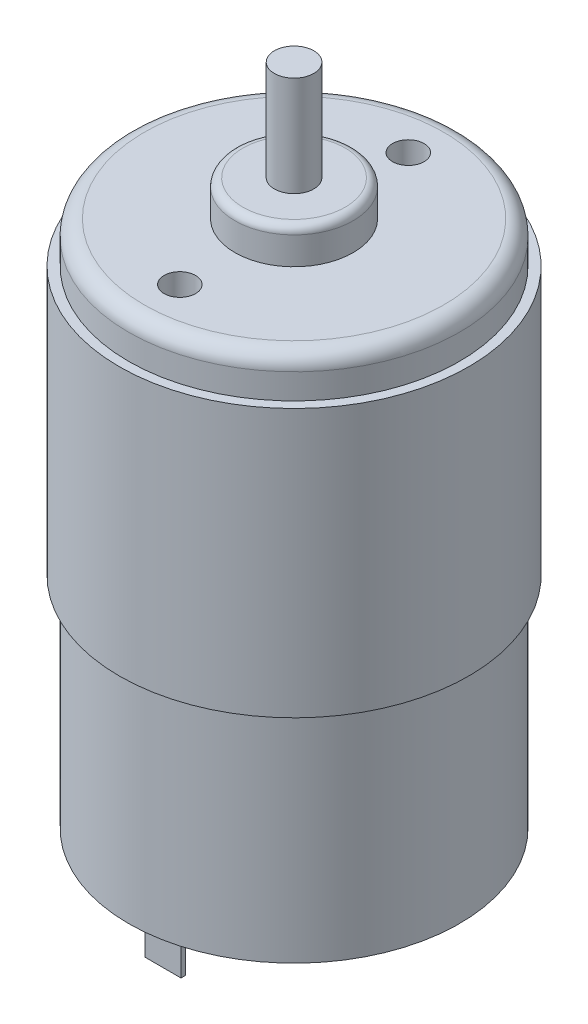
SolidWorks part; units mm, degrees
ref_plane "정면" through (0, 0, 0) normal (0, 0, 1) x (1, 0, 0)
ref_plane "윗면" through (0, 0, 0) normal (0, 1, 0) x (1, 0, 0)
ref_plane "우측면" through (0, 0, 0) normal (1, 0, 0) x (0, 0, -1)
sketch "스케치1" plane through (0, 0, 0) normal (0, 1, 0) x (1, 0, 0)
  circle A0 centre (0, 0) radius 21
  dimension "D1" = 42
extrude "보스-돌출1" add sketch "스케치1" along normal blind 67
sketch "스케치3" plane through (0, 67, 0) normal (0, 1, 0) x (1, 0, 0)
  circle A0 centre (0, 0) radius 7.5
  dimension "D1" = 15
extrude "보스-돌출3" add sketch "스케치3" along normal blind 4.5
sketch "스케치4" plane through (0, 71.5, 0) normal (0, 1, 0) x (1, 0, 0)
  circle A0 centre (0, 0) radius 2.5
  dimension "D1" = 5
extrude "보스-돌출4" add sketch "스케치4" along normal blind 12.7
fillet "필렛1" radius 2 1 edges at (0, 67, 21)
fillet "필렛2" radius 1 1 edges at (0, 71.5, 7.5)
sketch "스케치15" plane through (0, 67, 0) normal (0, 1, 0) x (1, 0, 0)
  line L0 (0, 0) -> (0, 14.5) construction
  line L1 (0, 0) -> (0, -14.5) construction
  circle A0 centre (0, 14.5) radius 2
  circle A1 centre (0, -14.5) radius 2
  dimension "D2" = 4
  dimension "D1" = 29
extrude "컷-돌출2" cut sketch "스케치15" against normal blind 5
sketch "스케치18" plane through (0, 0, 0) normal (0, -1, 0) x (1, 0, 0)
  line L0 (0, 0) -> (0, 16.35) construction
  line L1 (0, 0) -> (0, -16.35) construction
  line L2 (-2.3, 16.65) -> (-2.3, 16.05)
  line L3 (-2.3, 16.65) -> (2.3, 16.65)
  line L4 (-2.3, 16.05) -> (2.3, 16.05)
  line L5 (2.3, 16.65) -> (2.3, 16.05)
  line L6 (-2.3, 16.65) -> (2.3, 16.05) construction
  line L7 (-2.3, 16.05) -> (2.3, 16.65) construction
  line L8 (2.3, -16.65) -> (-2.3, -16.65)
  line L9 (2.3, -16.65) -> (2.3, -16.05)
  line L10 (-2.3, -16.65) -> (-2.3, -16.05)
  line L11 (2.3, -16.05) -> (-2.3, -16.05)
  line L12 (2.3, -16.65) -> (-2.3, -16.05) construction
  line L13 (-2.3, -16.65) -> (2.3, -16.05) construction
  dimension "D1" = 32.7
  dimension "D2" = 0.6
  dimension "D3" = 4.6
  dimension "D4" = 0.6
extrude "보스-돌출11" add sketch "스케치18" along normal blind 7
sketch "스케치19" plane through (0, 0, 0) normal (0, -1, 0) x (1, 0, 0)
  circle A0 centre (0, 0) radius 7.6
  dimension "D1" = 15.2
extrude "보스-돌출12" add sketch "스케치19" along normal blind 7
sketch "스케치20" plane through (0, 67, 0) normal (0, 1, 0) x (1, 0, 0)
  circle A0 centre (0, 0) radius 21
  circle A1 centre (0, 0) radius 22.175
  dimension "D1" = 44.35
extrude "보스-돌출13" add sketch "스케치20" against normal blind 34 from offset 5.2 offset against normal yes
